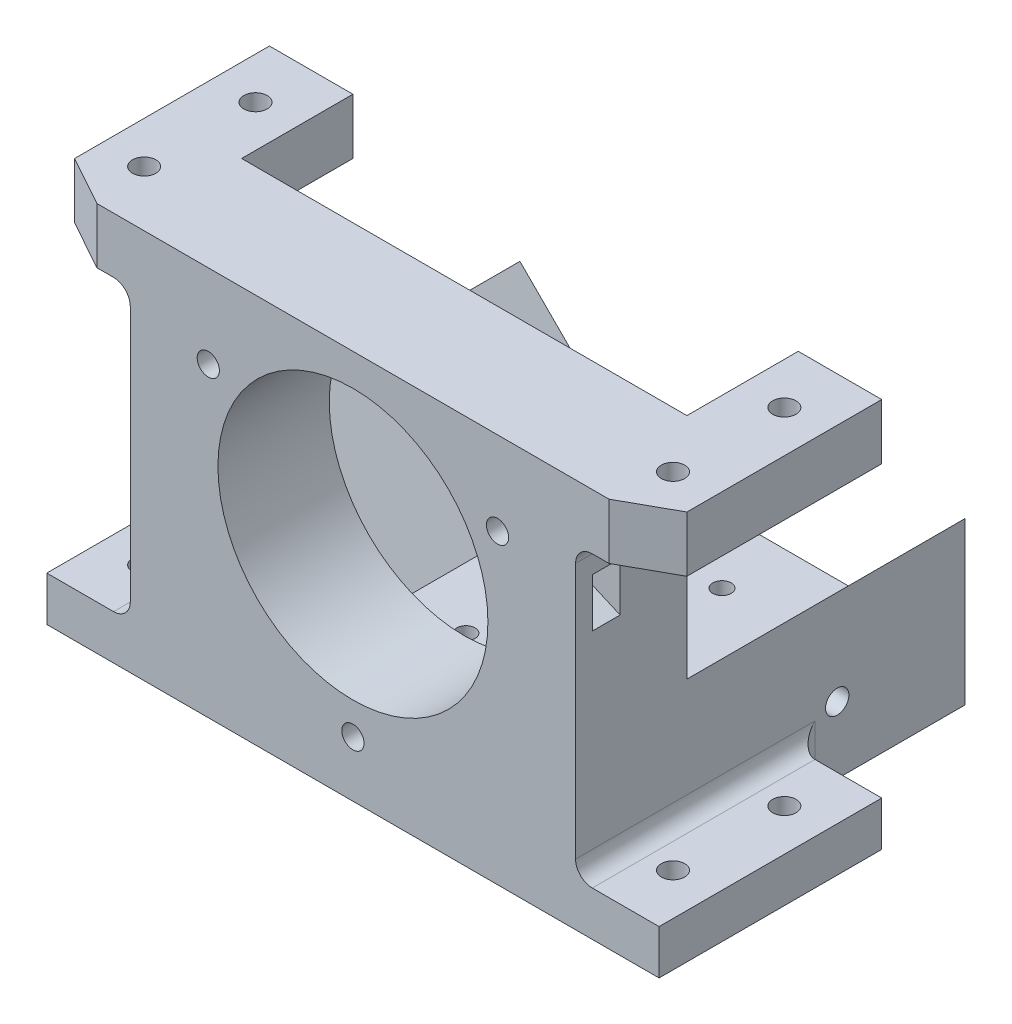
SolidWorks part; units mm, degrees
ref_plane "Front Plane" through (0, 0, 0) normal (0, 0, 1) x (1, 0, 0)
ref_plane "Top Plane" through (0, 0, 0) normal (0, 1, 0) x (1, 0, 0)
ref_plane "Right Plane" through (0, 0, 0) normal (1, 0, 0) x (0, 0, -1)
sketch "Sketch1" plane through (0, 0, 0) normal (0, 0, 1) x (1, 0, 0)
  line L1 (-40, -30) -> (40, -30)
  line L2 (-40, -30) -> (-40, 30)
  line L3 (-40, 30) -> (40, 30)
  line L4 (40, -30) -> (40, 30)
  line L5 (-40, -30) -> (40, 30) construction
  line L6 (-40, 30) -> (40, -30) construction
  circle A0 centre (0, 0) radius 24.25
  dimension "D1" = 48.5
  dimension "D2" = 80
  dimension "D3" = 60
extrude "Boss-Extrude1" add sketch "Sketch1" along normal blind 20
sketch "Sketch4" plane through (40, 0, 0) normal (1, 0, 0) x (0, 0, -1)
  line L0 (0, -30) -> (0, 30) construction
  line L1 (-20, 30) -> (0, 30)
  line L2 (-20, 30) -> (-20, 20)
  line L3 (-20, 20) -> (0, 20)
  line L5 (-20, 30) -> (0, 20) construction
  line L6 (-20, 20) -> (0, 30) construction
  line L8 (0, 30) -> (20, 30)
  line L10 (0, 20) -> (20, 20)
  line L11 (20, 30) -> (20, 20)
  line L12 (0, 30) -> (20, 20) construction
  line L13 (0, 20) -> (20, 30) construction
  point P4 (-10, 25)
  point P10 (10, 25)
  dimension "D1" = 10
extrude "Boss-Extrude3" add sketch "Sketch4" along normal blind 15
sketch "Sketch5" plane through (0, 30, 0) normal (0, 1, 0) x (1, 0, 0)
  line L0 (-40, -10) -> (55, -10) construction
  line L1 (55, 20) -> (55, -20) construction
  line L2 (46, -20) -> (55, -15)
  line L3 (40, 0) -> (40, -20) construction
  line L4 (40, 0) -> (-40, 0) construction
  line L5 (55, -20) -> (-40, -20) construction
  line L6 (-40, -20) -> (-40, 0) construction
  line L7 (55, 20) -> (55, -20) construction
  line L8 (40, 0) -> (55, 0) construction
  line L9 (55, -15) -> (55, -20)
  line L10 (55, -20) -> (46, -20)
  circle A0 centre (47.5, -10) radius 2.1
  circle A1 centre (47.5, 10) radius 2.1
  dimension "D1" = 4.2
  dimension "D2" = 7.5
  dimension "D3" = 9
  dimension "D4" = 5
extrude "Cut-Extrude2" cut sketch "Sketch5" against normal up to surface (10 mm away) up to face at (46, 20, 0)
sketch "Sketch6" plane through (0, -30, 0) normal (0, -1, 0) x (-1, 0, 0)
  line L1 (40, -20) -> (-40, -20)
  line L2 (40, -20) -> (40, 0)
  line L3 (40, 0) -> (-40, 0)
  line L4 (-40, -20) -> (-40, 0)
  line L5 (40, -20) -> (-40, 0) construction
  line L6 (40, 0) -> (-40, -20) construction
  point P4 (0, -10)
extrude "Boss-Extrude4" add sketch "Sketch6" along normal blind 2
sketch "Sketch8" plane through (0, 0, 0) normal (0, 0, -1) x (-1, 0, 0)
  line L0 (-40, -11) -> (-19, -32)
  line L1 (-40, -32) -> (-40, 20) construction
  line L2 (40, -32) -> (-40, -32) construction
  line L3 (-19, -32) -> (-40, -32)
  line L4 (-40, -32) -> (-40, -11)
  dimension "D1" = 21
extrude "Boss-Extrude6" add sketch "Sketch8" along normal blind 50
sketch "Sketch9" plane through (40, 0, 0) normal (1, 0, 0) x (0, 0, -1)
  line L0 (-20, -32) -> (-20, 20) construction
  line L1 (50, -32) -> (-20, -32) construction
  circle A0 centre (27, -28) radius 2.1
  dimension "D1" = 4.2
  dimension "D2" = 47
  dimension "D3" = 4
extrude "Cut-Extrude3" cut sketch "Sketch9" against normal through all
ref_plane "Plane1" through (19, 0, 0) normal (-1, 0, 0) x (0, 0, 1)
sketch "Sketch12" plane through (0, -32, 0) normal (0, -1, 0) x (1, 0, 0)
  line L0 (0, 20) -> (0, -50) construction
  line L1 (-40, 20) -> (40, 20)
  line L2 (-40, 20) -> (-40, -50)
  line L3 (-40, -50) -> (40, -50)
  line L4 (40, 20) -> (40, -50)
  line L5 (-40, 20) -> (40, -50) construction
  line L6 (-40, -50) -> (40, 20) construction
  line L7 (-8, -8.3) -> (8, -8.3) construction
  line L8 (-8, -8.3) -> (-8, -38.3) construction
  line L9 (-8, -38.3) -> (8, -38.3) construction
  line L10 (8, -38.3) -> (8, -8.3) construction
  line L11 (-40, 0) -> (19, 0) construction
  circle A0 centre (-8, -8.3) radius 1.65
  circle A1 centre (8, -8.3) radius 1.65
  circle A2 centre (8, -38.3) radius 1.65
  circle A3 centre (-8, -38.3) radius 1.65
  point P4 (0, -15)
  point P11 (0, -8.3)
  dimension "D4" = 3.3
  dimension "D1" = 16
  dimension "D2" = 30
  dimension "D3" = 8.3
extrude "Boss-Extrude8" add sketch "Sketch12" along normal blind 8
ref_plane "Plane2" through (0, 0, 0) normal (1, 0, 0) x (0, 0, -1)
mirror "Mirror1" about plane through (0, 0, 0) normal (1, 0, 0) of "Cut-Extrude3", "Boss-Extrude6", "Boss-Extrude4", "Cut-Extrude2", "Boss-Extrude3"
sketch "Sketch13" plane through (-40, 0, 0) normal (-1, 0, 0) x (0, 0, 1)
  line L0 (20, 20) -> (20, -40) construction
  line L1 (20, -40) -> (0, -40)
  line L2 (20, -40) -> (20, -32)
  line L3 (20, -32) -> (0, -32)
  line L5 (20, -40) -> (0, -32) construction
  line L6 (20, -32) -> (0, -40) construction
  line L7 (15, 20) -> (-20, 20) construction
  line L13 (-20, -40) -> (0, -40)
  line L14 (-20, -40) -> (-20, -32)
  line L15 (-20, -32) -> (0, -32)
  line L17 (-20, -40) -> (0, -32) construction
  line L18 (-20, -32) -> (0, -40) construction
  point P4 (10, -36)
  point P15 (-10, -36)
  dimension "D1" = 8
  dimension "D2" = 52
  dimension "D3" = 20
extrude "Boss-Extrude9" add sketch "Sketch13" along normal blind 15
sketch "Sketch14" plane through (0, -40, 0) normal (0, -1, 0) x (1, 0, 0)
  line L0 (-55, 0) -> (-27.8806, 0) construction
  line L1 (-55, -20) -> (-55, 20) construction
  circle A0 centre (-47.5, 10) radius 2.1
  circle A1 centre (-47.5, 10) radius 2.1 construction
  circle A2 centre (-47.5, -10) radius 2.1
extrude "Cut-Extrude4" cut sketch "Sketch14" against normal blind 10
mirror "Mirror2" about plane through (0, 0, 0) normal (1, 0, 0) of "Cut-Extrude4", "Boss-Extrude9"
sketch "Sketch15" plane through (0, -40, 0) normal (0, -1, 0) x (1, 0, 0)
  line L0 (-8, -8.3) -> (8, -8.3) construction
  line L1 (-55, 20) -> (55, 20)
  line L2 (-55, 20) -> (-55, -20)
  line L3 (-55, -20) -> (55, -20)
  line L4 (55, 20) -> (55, -20)
  line L5 (-55, 20) -> (55, -20) construction
  line L6 (-55, -20) -> (55, 20) construction
  line L7 (-8, -3.3) -> (8, -3.3)
  line L8 (-8, -13.3) -> (8, -13.3)
  circle A0 centre (-47.5, 10) radius 2.1
  circle A1 centre (-47.5, -10) radius 2.0834
  circle A2 centre (47.5, -10) radius 2
  circle A3 centre (47.5, 10) radius 2
  circle A4 centre (-47.5, 10) radius 2.1 construction
  arc A24 (-8, -3.3) -> (-8, -13.3) centre (-8, -8.3) ccw
  arc A25 (8, -13.3) -> (8, -3.3) centre (8, -8.3) ccw
  circle A26 centre (8, -8.3) radius 1.65 construction
  point P4 (0, 0)
  point P19 (0, -8.3)
  point P24 (13, -8.3)
  dimension "D1" = 5
sketch "Sketch16" plane through (0, 0, 20) normal (0, 0, 1) x (1, 0, 0)
  line L0 (0, -34.1) -> (0, 34.1) construction
  line L1 (0, -30) -> (0, -24.25) construction
  line L2 (0, 0) -> (0, -30) construction
  circle A0 centre (0, -30) radius 2
  circle A1 centre (0, 0) radius 24.25 construction
  dimension "D1" = 4
  dimension "D2" = 30
extrude "Cut-Extrude5" cut sketch "Sketch16" against normal blind 3
pattern_circular "CirPattern1" count 3 over 360 about axis through (0, 0, 0) along (0, 0, 1) of "Cut-Extrude5"
fillet "Fillet1" radius 3 6 edges at (40, 20, 10) (40, -32, 0) (-40, 20, 10) (-40, -32, 0) (-40, -36, -20) (40, -36, -20)
ref_plane "Plane3" through (0, 0, 17) normal (0, 0, 1) x (1, 0, 0)
sketch "Sketch17" plane through (0, 0, 17) normal (0, 0, 1) x (1, 0, 0)
  line L0 (-3.6, -32.0785) -> (-3.6, -40)
  line L2 (29.323, 17.4717) -> (25.5113, 19.1303)
  line L3 (25.5113, 19.1303) -> (22.1691, 16.6586)
  line L4 (22.1691, 16.6586) -> (22.6385, 12.5283)
  line L5 (22.6385, 12.5283) -> (26.4502, 10.8697)
  line L7 (-21.9156, 15.8688) -> (-24.7006, 18.9549)
  line L8 (-24.7006, 18.9549) -> (-28.7657, 18.0861)
  line L11 (-27.2609, 11.0451) -> (-23.1958, 11.9139)
  line L12 (-23.1958, 11.9139) -> (-21.9156, 15.8688)
  line L14 (3.6, -32.0785) -> (3.6, -27.9215)
  line L15 (3.6, -27.9215) -> (0, -25.8431)
  line L16 (0, -25.8431) -> (-3.6, -27.9215)
  line L17 (-3.6, -27.9215) -> (-3.6, -32.0785)
  line L19 (55, -40) -> (-55, -40) construction
  line L20 (-3.6, -40) -> (3.6, -40)
  line L21 (3.6, -40) -> (3.6, -32.0785)
  line L22 (-1.8, -33.1177) -> (0, -34.1569) [skipped]
  line L23 (1.8, -33.1177) -> (3.6, -32.0785) [skipped]
  line L24 (-28.7657, 18.0861) -> (-43.6793, 14.9989)
  line L25 (-43.6793, 14.9989) -> (-42.2199, 7.9485)
  line L26 (-42.2199, 7.9485) -> (-27.2609, 11.0451)
  line L27 (26.4502, 10.8697) -> (42.4595, 3.9032)
  line L28 (-28.7657, 18.0861) -> (-29.4058, 16.1086) [skipped]
  line L29 (-28.6534, 12.5881) -> (-27.2609, 11.0451) [skipped]
  line L30 (42.4595, 3.9032) -> (45.8518, 11.699)
  line L31 (45.8518, 11.699) -> (29.323, 17.4717)
  line L33 (29.7924, 13.3414) -> (29.5577, 15.4065) [skipped]
  line L34 (26.4502, 10.8697) -> (28.1213, 12.1055) [skipped]
  circle A0 centre (25.9808, 15) radius 3.6 construction
  circle A1 centre (-25.9808, 15) radius 3.6 construction
  circle A2 centre (0, -30) radius 3.6 construction
  dimension "D1" = 7.2
  dimension "D2" = 7.2
  dimension "D3" = 7.2
  dimension "D4" = 90
extrude "Cut-Extrude6" cut sketch "Sketch17" against normal blind 5
